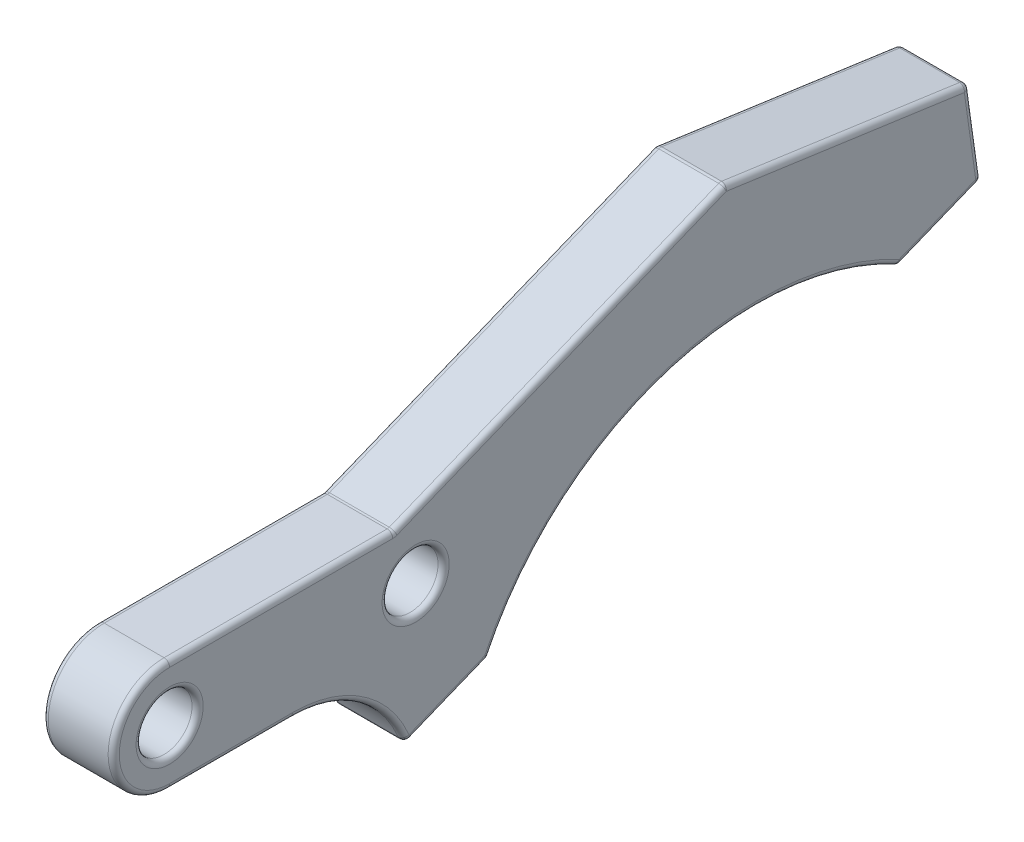
SolidWorks part; units mm, degrees
material "AISI 304"
ref_plane "Plano frontal" through (0, 0, 0) normal (0, 0, 1) x (1, 0, 0)
ref_plane "Plano superior" through (0, 0, 0) normal (0, 1, 0) x (1, 0, 0)
ref_plane "Plano direito" through (0, 0, 0) normal (1, 0, 0) x (0, 0, -1)
sketch "Esboço2" plane through (0, 0, 0) normal (1, 0, 0) x (0, 0, -1)
  line L0 (-26.5167, 0) -> (-4.5167, 0) construction
  line L1 (-26.5167, 5) -> (-6.4667, 5)
  line L2 (-26.5167, -5) -> (-15.5167, -5)
  line L3 (-6.4667, 5) -> (23.2033, 16.9875)
  line L4 (23.2033, 16.9875) -> (44.9933, 13.9251)
  line L5 (44.9933, 13.9251) -> (46.1176, 5.9251)
  line L6 (46.1176, 5.9251) -> (38.7002, 2.9282)
  line L7 (2.0244, -9.0749) -> (-5.3931, -12.0718)
  arc A0 (-26.5167, 5) -> (-26.5167, -5) centre (-26.5167, 0) ccw
  circle A2 centre (-26.5167, 0) radius 2.5
  circle A3 centre (-4.5167, 0) radius 2.5
  arc A4 (38.7002, 2.9282) -> (2.0244, -9.0749) centre (26.0543, -20.4654) ccw
  arc A5 (-5.3931, -12.0718) -> (-15.5167, -5) centre (-15.5167, -15.7821) ccw
  point P3 (-15.5167, 0)
  point P5 (0, 0)
  dimension "D2" = 5
  dimension "D3" = 22
  dimension "D14" = 38.59
  dimension "D15" = 5
  dimension "D1" = 10
  dimension "D4" = 158
  dimension "D5" = 20.05
  dimension "D6" = 29.67
  dimension "D7" = 30
  dimension "D8" = 254
  dimension "D9" = 21.79
  dimension "D10" = 8
  dimension "D11" = 8
  dimension "D12" = 8
  dimension "D13" = 7.03
extrude "Ressalto-extrusão1" add sketch "Esboço2" along normal mid plane 6.35
fillet "Filete1" radius 0.5 30 edges at (3.175, 0, 31.5167) (-3.175, 0, 31.5167) (3.175, 0, 24.0167) (3.175, 5, 16.4917) (-3.175, 5, 16.4917) (3.175, 15.4563, -34.0983) (-3.175, 15.4563, -34.0983) (0, 16.9875, -23.2033) (3.175, 10.9937, -8.3683) (0, 5, 6.4667) (-3.175, 10.9937, -8.3683) (3.175, 4.4266, -42.4089) (-3.175, 4.4266, -42.4089) (0, 5.9251, -46.1176) (3.175, 9.9251, -45.5555) (0, 13.9251, -44.9933) (-3.175, 9.9251, -45.5555) (3.175, -5, 21.0167) (-3.175, -5, 21.0167) (3.175, -6.943, 9.3422) (-3.175, -6.943, 9.3422) (0, -12.0718, 5.3931) (3.175, -10.5733, 1.6843) (-3.175, -10.5733, 1.6843) (0, -9.0749, -2.0244) (3.175, 4.8083, -17.7828) (0, 2.9282, -38.7002) (-3.175, 4.8083, -17.7828) (-3.175, 0, 2.0167) (3.175, 0, 2.0167)
